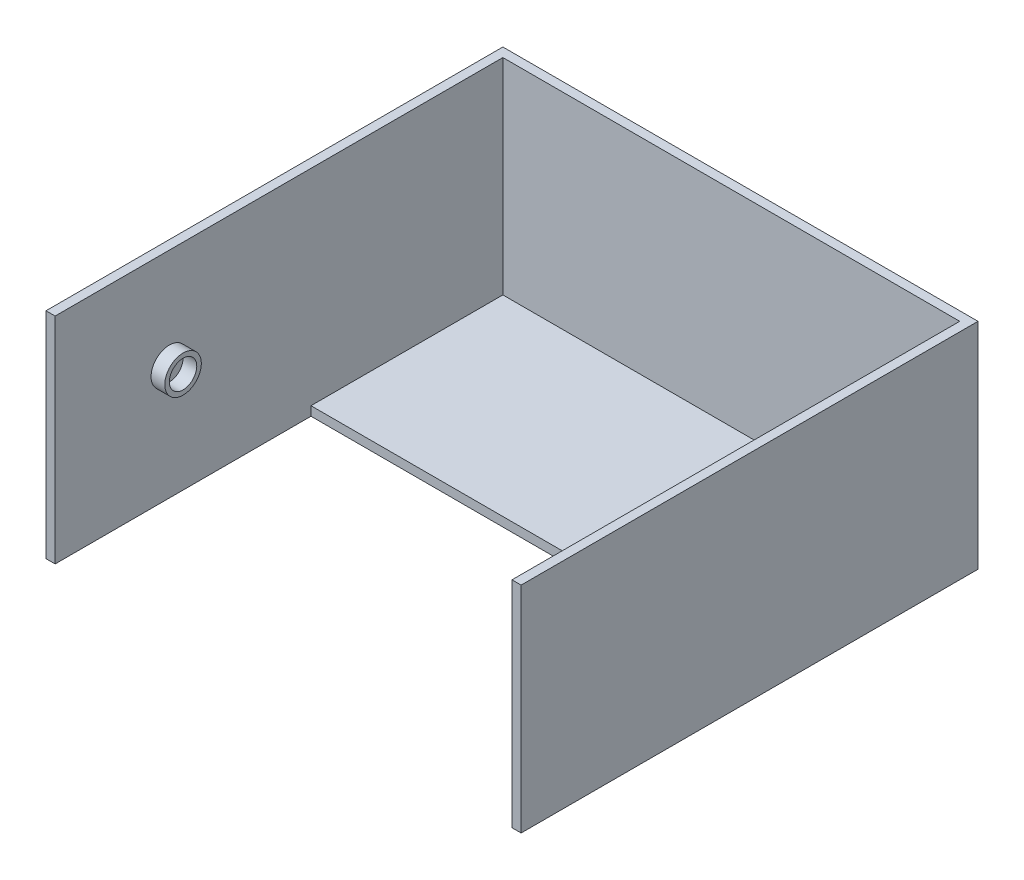
SolidWorks part; units mm, degrees
ref_plane "前视基准面" through (0, 0, 0) normal (0, 0, 1) x (1, 0, 0)
ref_plane "上视基准面" through (0, 0, 0) normal (0, 1, 0) x (1, 0, 0)
ref_plane "右视基准面" through (0, 0, 0) normal (1, 0, 0) x (0, 0, -1)
sketch "草图1" plane through (0, 0, 0) normal (0, 0, 1) x (1, 0, 0)
  line L0 (-48.2423, 18.1274) -> (-48.2423, -28.8726)
  line L1 (-48.2423, -28.8726) -> (55.7577, -28.8726)
  line L2 (55.7577, -28.8726) -> (55.7577, 18.1274)
extrude "拉伸-薄壁1" add sketch "草图1" against normal blind 100 thin contours L0 L1 L2 thin type one direction reverse wall 2
ref_plane "基准面1" through (55.7577, -28.8726, -100) normal (0, 0, 1) x (1, 0, 0)
sketch "草图5" plane through (0, -26.8726, 0) normal (0, 1, 0) x (1, 0, 0)
  line L0 (53.7577, 100) -> (53.7577, 0) construction
  line L1 (-46.2423, 100) -> (53.7577, 100)
  line L2 (-46.2423, 100) -> (-46.2423, 98)
  line L3 (-46.2423, 98) -> (53.7577, 98)
  line L4 (53.7577, 100) -> (53.7577, 98)
extrude "凸台-拉伸1" add sketch "草图5" along normal blind 45
sketch "草图6" plane through (0, -26.8726, 0) normal (0, 1, 0) x (1, 0, 0)
  line L1 (-46.2423, 0) -> (53.7577, 0)
  line L2 (-46.2423, 0) -> (-46.2423, 56)
  line L3 (-46.2423, 56) -> (53.7577, 56)
  line L4 (53.7577, 0) -> (53.7577, 56)
  dimension "D1" = 100
  dimension "D2" = 56
extrude "切除-拉伸1" cut sketch "草图6" against normal through all
sketch "草图7" plane through (-46.2423, 0, 0) normal (1, 0, 0) x (0, 0, -1)
  circle A0 centre (25, -3.8726) radius 4
  point P5 (0, 18.1274)
  dimension "D1" = 8
  dimension "D2" = 25
  dimension "D3" = 22
extrude "拉伸-薄壁2" add sketch "草图7" along normal blind 3 thin thin type one direction reverse wall 1
ref_plane "基准面2" through (3.7577, 0, 0) normal (1, 0, 0) x (0, 0, -1)
mirror "镜向1" about plane through (3.7577, 0, 0) normal (1, 0, 0) of "拉伸-薄壁2"
